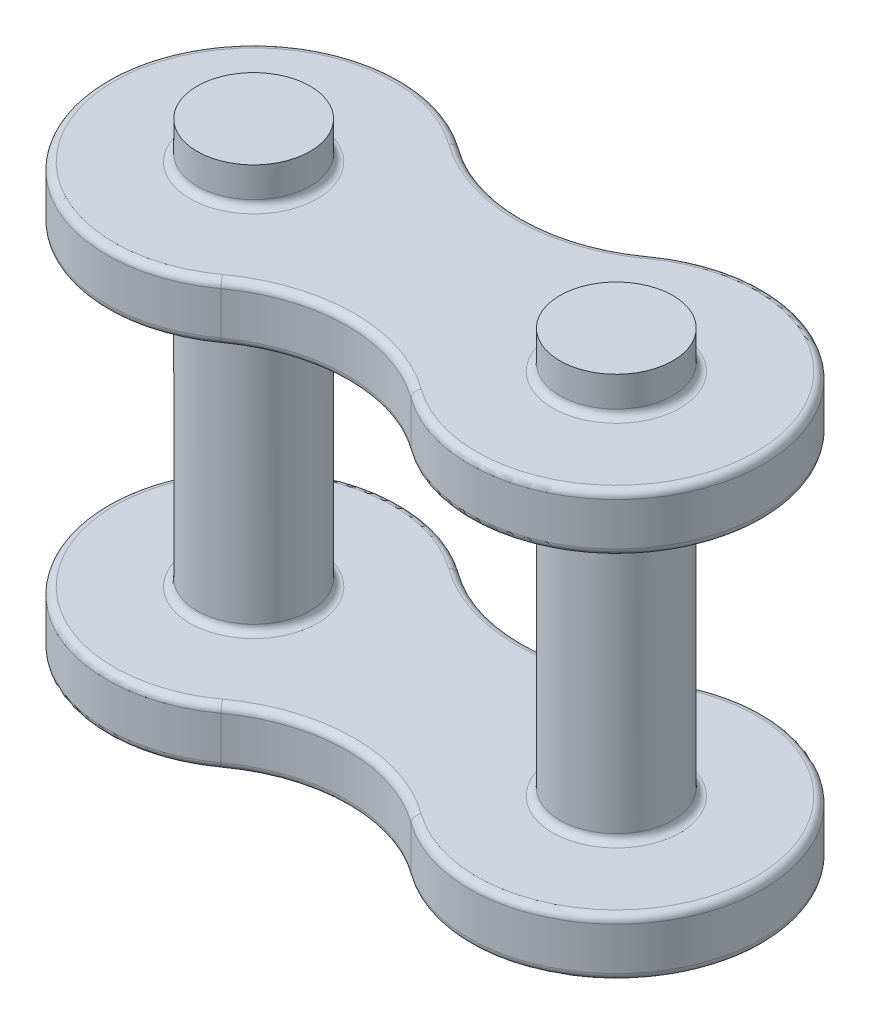
SolidWorks part; units mm, degrees
material "Alloy Steel"
ref_plane "X-Y Datum" through (0, 0, 0) normal (0, 0, 1) x (1, 0, 0)
ref_plane "X-Z Datum" through (0, 0, 0) normal (0, 1, 0) x (1, 0, 0)
ref_plane "Y-Z Datum" through (0, 0, 0) normal (1, 0, 0) x (0, 0, -1)
sketch "Sketch2" plane through (0, 0, 0) normal (0, 1, 0) x (1, 0, 0)
  line L0 (0, -9.7123) -> (0, 9.7123) construction
  line L1 (12.7033, 0) -> (-12.7033, 0) construction
  circle A0 centre (-6.35, 0) radius 1.98
  arc A1 (-3.3293, 4.163) -> (-3.3293, -4.163) centre (-6.35, 0) ccw
  circle A2 centre (6.35, 0) radius 1.98
  arc A3 (3.3293, 4.163) -> (3.3293, -4.163) centre (6.35, 0) cw
  arc A4 (-3.3293, 4.163) -> (3.3293, 4.163) centre (0, 8.7513) ccw
  arc A5 (-3.3293, -4.163) -> (3.3293, -4.163) centre (0, -8.7513) cw
  point P4 (0, 0)
  point P8 (0, 0)
  dimension "D1" = 10.287
  dimension "D2" = 3.96
  dimension "D3" = 6.35
extrude "Boss-Extrude1" add sketch "Sketch2" along normal mid plane 2.0066
ref_plane "Center Plane" through (0, 6.4389, 0) normal (0, 1, 0) x (1, 0, 0)
sketch "Sketch5" plane through (0, 6.4389, 0) normal (0, 1, 0) x (1, 0, 0)
  line L0 (0, -55) -> (0, 55) construction
  circle A0 centre (-6.35, 0) radius 1.98 construction
  circle A1 centre (-6.35, 0) radius 1.98
  circle A2 centre (6.35, 0) radius 1.98
extrude "Boss-Extrude2" add sketch "Sketch5" along normal mid plane 17.5006
fillet "Fillet1" radius 0.254 12 edges at (11.4935, -1.0033, 0) (0, -1.0033, 3.0824) (-11.4935, -1.0033, 0) (0, 1.0033, -3.0824) (11.4935, 1.0033, 0) (0, 1.0033, 3.0824) (-6.35, -1.0033, 1.98) (6.35, -1.0033, 1.98) (6.35, 1.0033, -1.98) (-6.35, 1.0033, 1.98) (0, -1.0033, -3.0824) (-11.4935, 1.0033, 0)
mirror "Mirror1" about plane through (0, 6.4389, 0) normal (0, 1, 0) of "Fillet1", "Boss-Extrude1"
